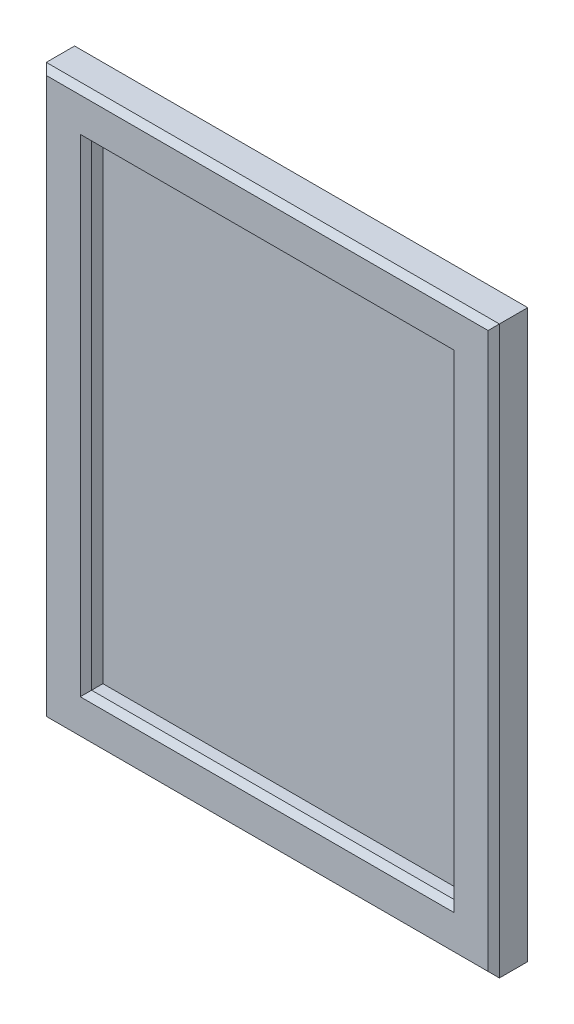
SolidWorks part; units mm, degrees
ref_plane "Спереди" through (0, 0, 0) normal (0, 0, 1) x (1, 0, 0)
ref_plane "Сверху" through (0, 0, 0) normal (0, 1, 0) x (1, 0, 0)
ref_plane "Справа" through (0, 0, 0) normal (1, 0, 0) x (0, 0, -1)
other "Configuration Table"
sketch "Эскиз1" plane through (0, 0, 0) normal (0, 0, 1) x (1, 0, 0)
  line L0 (80, 80) -> (80, 920)
  line L1 (0, 0) -> (800, 0)
  line L2 (0, 0) -> (0, 1000)
  line L3 (0, 1000) -> (800, 1000)
  line L4 (800, 0) -> (800, 1000)
  line L5 (80, 920) -> (720, 920)
  line L6 (720, 80) -> (720, 920)
  line L7 (80, 80) -> (720, 80)
  dimension "D1" = 800
  dimension "D3" = 1000
  dimension "D2" = 80
extrude "Бобышка-Вытянуть1" add sketch "Эскиз1" along normal blind 60
chamfer "Фаска1" distance 10 angle 45 8 edges at (720, 500, 60) (400, 920, 60) (80, 500, 60) (400, 80, 60) (400, 1000, 60) (800, 500, 60) (400, 0, 60) (0, 500, 60)
sketch "Эскиз2" plane through (0, 0, 0) normal (0, 0, -1) x (-1, 0, 0)
  line L1 (-737.3097, 953.4569) -> (-41.8597, 953.4569)
  line L2 (-737.3097, 953.4569) -> (-737.3097, 37.5134)
  line L3 (-737.3097, 37.5134) -> (-41.8597, 37.5134)
  line L4 (-41.8597, 953.4569) -> (-41.8597, 37.5134)
  point P4 (-737.3097, 953.4569)
extrude "Бобышка-Вытянуть2" add sketch "Эскиз2" against normal blind 10 from offset 20 separate body
